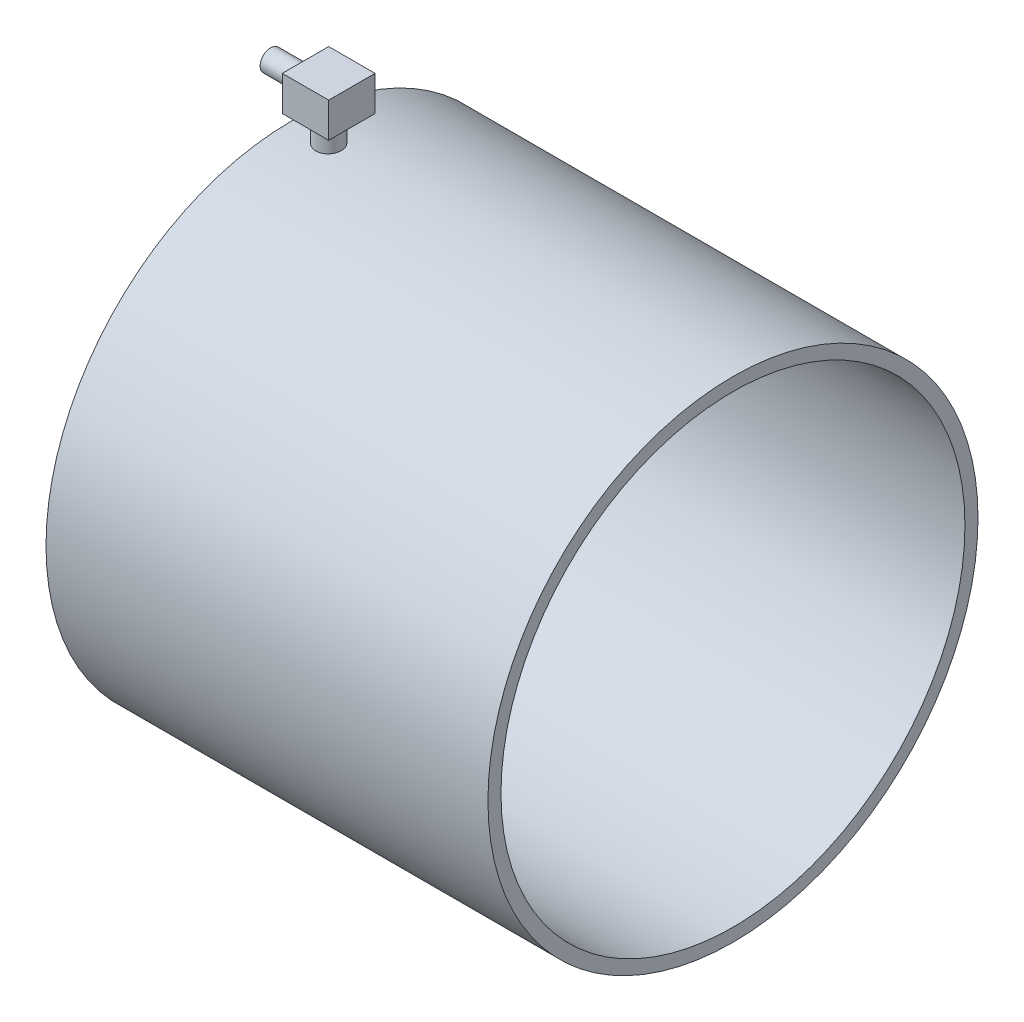
SolidWorks part; units mm, degrees
ref_plane "Front Plane" through (0, 0, 0) normal (0, 0, 1) x (1, 0, 0)
ref_plane "Top Plane" through (0, 0, 0) normal (0, 1, 0) x (1, 0, 0)
ref_plane "Right Plane" through (0, 0, 0) normal (1, 0, 0) x (0, 0, -1)
sketch "Sketch1" plane through (0, 0, 0) normal (1, 0, 0) x (0, 0, -1)
  circle A0 centre (0, 0) radius 21.125
  circle A1 centre (0, 0) radius 20
extrude "Boss-Extrude1" add sketch "Sketch1" along normal blind 38.1 contours A0 | A1
ref_plane "Plane1" through (0, 20.3301, 0) normal (0, 1, 0) x (1, 0, 0)
sketch "Sketch2" plane through (0, 20.3301, 0) normal (0, 1, 0) x (1, 0, 0)
  circle A0 centre (3.2449, 0) radius 1.1044
extrude "Boss-Extrude2" add sketch "Sketch2" along normal blind 3 separate body
sketch "Sketch3" plane through (0, 23.3301, 0) normal (0, 1, 0) x (1, 0, 0)
  line L1 (5.2449, 2) -> (1.2449, 2)
  line L2 (5.2449, 2) -> (5.2449, -2)
  line L3 (5.2449, -2) -> (1.2449, -2)
  line L4 (1.2449, 2) -> (1.2449, -2)
  line L5 (5.2449, 2) -> (1.2449, -2) construction
  line L6 (5.2449, -2) -> (1.2449, 2) construction
  point P0 (3.2449, 0)
  dimension "D1" = 4
  dimension "D2" = 4
extrude "Boss-Extrude3" add sketch "Sketch3" along normal blind 3
sketch "Sketch4" plane through (1.2449, 0, 0) normal (-1, 0, 0) x (0, 0, 1)
  circle A0 centre (0, 24.8301) radius 0.9133
  circle A1 centre (0, 24.8301) radius 0.6619
  point P3 (0, 0)
extrude "Boss-Extrude4" add sketch "Sketch4" along normal blind 3
